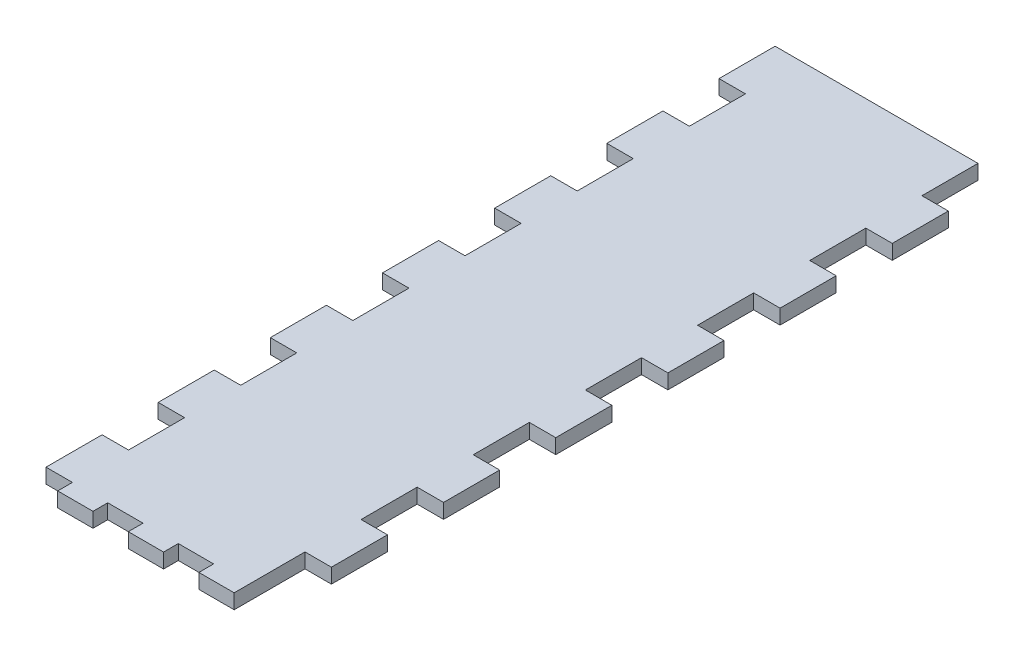
SolidWorks part; units mm, degrees
ref_plane "Front Plane" through (0, 0, 0) normal (0, 0, 1) x (1, 0, 0)
ref_plane "Top Plane" through (0, 0, 0) normal (0, 1, 0) x (1, 0, 0)
ref_plane "Right Plane" through (0, 0, 0) normal (1, 0, 0) x (0, 0, -1)
sketch "Sketch1" plane through (0, 0, 0) normal (0, 1, 0) x (1, 0, 0)
  line L104 (80.0182, -34.385) -> (87.6882, -34.385)
  line L105 (87.6882, -34.385) -> (87.6882, -31.185)
  line L106 (87.6882, -31.185) -> (95.3582, -31.185)
  line L107 (95.3582, -31.185) -> (95.3582, -34.385)
  line L108 (95.3582, -34.385) -> (103.0282, -34.385)
  line L109 (103.0282, -34.385) -> (103.0282, -31.185)
  line L110 (103.0282, -31.185) -> (110.6981, -31.185)
  line L111 (110.6981, -31.185) -> (110.6981, -34.385)
  line L112 (110.6981, -34.385) -> (118.3681, -34.385)
  line L113 (80.0182, -34.385) -> (80.0182, -31.185)
  line L114 (80.0182, -31.185) -> (74.2756, -31.185)
  line L115 (74.2756, -31.185) -> (74.2756, -18.9967)
  line L116 (74.2756, -18.9967) -> (80.0182, -18.9967)
  line L117 (80.0182, -18.9967) -> (80.0182, -6.8084)
  line L118 (80.0182, -6.8084) -> (74.2756, -6.8084)
  line L121 (118.3681, -6.8084) -> (124.1107, -6.8084)
  line L122 (124.1107, -6.8084) -> (124.1107, -18.9967)
  line L123 (124.1107, -18.9967) -> (118.3681, -18.9967)
  line L124 (118.3681, -18.9967) -> (118.3681, -34.385)
  line L270 (74.2756, -6.8084) -> (74.2756, 5.3799)
  line L271 (74.2756, 5.3799) -> (80.0182, 5.3799)
  line L272 (80.0182, 5.3799) -> (80.0182, 17.5682)
  line L273 (80.0182, 17.5682) -> (74.2756, 17.5682)
  line L274 (74.2756, 17.5682) -> (74.2756, 29.7565)
  line L275 (74.2756, 29.7565) -> (80.0182, 29.7565)
  line L276 (80.0182, 29.7565) -> (80.0182, 41.9448)
  line L277 (80.0182, 41.9448) -> (74.2756, 41.9448)
  line L278 (74.2756, 41.9448) -> (74.2756, 54.1331)
  line L279 (74.2756, 54.1331) -> (80.0182, 54.1331)
  line L280 (80.0182, 54.1331) -> (80.0182, 66.3215)
  line L281 (80.0182, 66.3215) -> (74.2756, 66.3215)
  line L282 (74.2756, 66.3215) -> (74.2756, 78.5098)
  line L283 (74.2756, 78.5098) -> (80.0182, 78.5098)
  line L284 (80.0182, 78.5098) -> (80.0182, 90.6981)
  line L285 (80.0182, 90.6981) -> (74.2756, 90.6981)
  line L286 (74.2756, 90.6981) -> (74.2756, 102.8864)
  line L287 (74.2756, 102.8864) -> (80.0182, 102.8864)
  line L288 (80.0182, 102.8864) -> (80.0182, 115.0747)
  line L289 (80.0182, 115.0747) -> (74.2756, 115.0747)
  line L290 (74.2756, 115.0747) -> (74.2756, 127.263)
  line L291 (118.3681, -6.8084) -> (118.3681, 5.3799)
  line L292 (118.3681, 5.3799) -> (124.1107, 5.3799)
  line L293 (124.1107, 5.3799) -> (124.1107, 17.5682)
  line L294 (124.1107, 17.5682) -> (118.3681, 17.5682)
  line L295 (118.3681, 17.5682) -> (118.3681, 29.7565)
  line L296 (118.3681, 29.7565) -> (124.1107, 29.7565)
  line L297 (124.1107, 29.7565) -> (124.1107, 41.9448)
  line L298 (124.1107, 41.9448) -> (118.3681, 41.9448)
  line L299 (118.3681, 41.9448) -> (118.3681, 54.1331)
  line L300 (118.3681, 54.1331) -> (124.1107, 54.1331)
  line L301 (124.1107, 54.1331) -> (124.1107, 66.3215)
  line L302 (124.1107, 66.3215) -> (118.3681, 66.3215)
  line L303 (118.3681, 66.3215) -> (118.3681, 78.5098)
  line L304 (118.3681, 78.5098) -> (124.1107, 78.5098)
  line L305 (124.1107, 78.5098) -> (124.1107, 90.6981)
  line L306 (124.1107, 90.6981) -> (118.3681, 90.6981)
  line L307 (118.3681, 90.6981) -> (118.3681, 102.8864)
  line L308 (118.3681, 102.8864) -> (124.1107, 102.8864)
  line L309 (124.1107, 102.8864) -> (124.1107, 115.0747)
  line L310 (124.1107, 115.0747) -> (118.3681, 115.0747)
  line L311 (118.3681, 115.0747) -> (118.3681, 127.263)
  line L636 (118.3681, 127.263) -> (74.2756, 127.263)
  dimension "D11" = 12.1883
  dimension "D13" = 3.2
  dimension "D22" = 158.448
  dimension "D45" = 5.7426
  dimension "D66" = 38.3499
  dimension "D83" = 5.7426
  dimension "D86" = 15.3883
extrude "Boss-Extrude3" add sketch "Sketch1" along normal blind 3.2
equation "\"Thick\"=3.2"
equation "\"angletabwidth\"=4"
